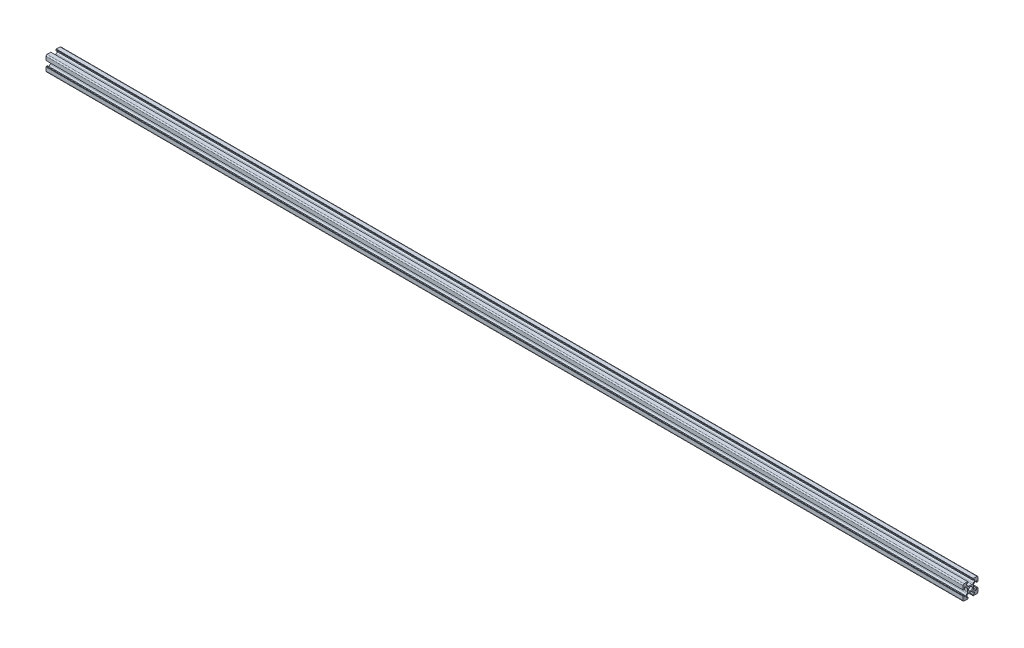
SolidWorks part; units mm, degrees
ref_plane "Front Plane" through (0, 0, 0) normal (1, 0, 0) x (0, 1, 0)
ref_plane "Top Plane" through (0, 0, 0) normal (0, 0, 1) x (0, 1, 0)
ref_plane "Right Plane" through (0, 0, 0) normal (0, 1, 0) x (-1, 0, 0)
sketch "Sketch2" plane through (0, 0, 0) normal (1, 0, 0) x (0, 1, 0)
  line L0 (-10, 3.6) -> (-9.5, 3.6)
  line L1 (-2.0109, -3.9) -> (2.0109, -3.9)
  line L2 (-3.9, -2.0109) -> (-3.9, 2.0109)
  line L3 (-2.0109, 3.9) -> (2.0109, 3.9)
  line L4 (3.9, -2.0109) -> (3.9, 2.0109)
  line L5 (-3.9, -3.9) -> (3.9, 3.9) construction
  line L6 (-3.9, 3.9) -> (3.9, -3.9) construction
  line L7 (-8.5, -10) -> (-3.6, -10)
  line L8 (-10, -8.5) -> (-10, -3.6)
  line L9 (-8.5, 10) -> (-3.6, 10)
  line L10 (10, -8.5) -> (10, -3.6)
  line L11 (-10, -10) -> (10, 10) construction
  line L12 (-10, 10) -> (10, -10) construction
  line L13 (-9.5, 3.6) -> (-9.5, 3.1)
  line L14 (-9.5, 3.1) -> (-8.2, 3.1)
  line L15 (-8.2, 3.1) -> (-8.2, 5.5)
  line L16 (-8.2, 5.5) -> (-6.5607, 5.5)
  line L17 (-6.5607, 5.5) -> (-4.4858, 3.4251)
  line L18 (3.6, 10) -> (3.6, 9.5)
  line L19 (-3.1, 9.5) -> (-3.1, 8.2)
  line L20 (-3.6, 9.5) -> (-3.1, 9.5)
  line L21 (-3.6, 10) -> (-3.6, 9.5)
  line L22 (-3.1, 8.2) -> (-5.5, 8.2)
  line L23 (-5.5, 8.2) -> (-5.5, 6.5607)
  line L24 (-5.5, 6.5607) -> (-3.4251, 4.4858)
  line L25 (3.6, 9.5) -> (3.1, 9.5)
  line L26 (3.1, 9.5) -> (3.1, 8.2)
  line L27 (3.1, 8.2) -> (5.5, 8.2)
  line L28 (5.5, 8.2) -> (5.5, 6.5607)
  line L29 (5.5, 6.5607) -> (3.4251, 4.4858)
  line L30 (6.5607, 5.5) -> (4.4858, 3.4251)
  line L31 (8.2, 5.5) -> (6.5607, 5.5)
  line L32 (8.2, 3.1) -> (8.2, 5.5)
  line L33 (9.5, 3.1) -> (8.2, 3.1)
  line L34 (9.5, 3.6) -> (9.5, 3.1)
  line L35 (10, 3.6) -> (9.5, 3.6)
  line L36 (10, -3.6) -> (9.5, -3.6)
  line L37 (9.5, -3.6) -> (9.5, -3.1)
  line L38 (9.5, -3.1) -> (8.2, -3.1)
  line L39 (8.2, -3.1) -> (8.2, -5.5)
  line L40 (8.2, -5.5) -> (6.5607, -5.5)
  line L41 (6.5607, -5.5) -> (4.4858, -3.4251)
  line L42 (5.5, -6.5607) -> (3.4251, -4.4858)
  line L43 (5.5, -8.2) -> (5.5, -6.5607)
  line L44 (3.1, -8.2) -> (5.5, -8.2)
  line L45 (3.1, -9.5) -> (3.1, -8.2)
  line L46 (3.6, -9.5) -> (3.1, -9.5)
  line L47 (3.6, -10) -> (3.6, -9.5)
  line L48 (-3.6, -10) -> (-3.6, -9.5)
  line L49 (-3.6, -9.5) -> (-3.1, -9.5)
  line L50 (-3.1, -9.5) -> (-3.1, -8.2)
  line L51 (-3.1, -8.2) -> (-5.5, -8.2)
  line L52 (-5.5, -8.2) -> (-5.5, -6.5607)
  line L53 (-5.5, -6.5607) -> (-3.4251, -4.4858)
  line L54 (-6.5607, -5.5) -> (-4.4858, -3.4251)
  line L55 (-8.2, -5.5) -> (-6.5607, -5.5)
  line L56 (-8.2, -3.1) -> (-8.2, -5.5)
  line L57 (-9.5, -3.1) -> (-8.2, -3.1)
  line L58 (-9.5, -3.6) -> (-9.5, -3.1)
  line L59 (-10, -3.6) -> (-9.5, -3.6)
  line L60 (-10, 3.6) -> (-10, 8.5)
  line L61 (3.6, 10) -> (8.5, 10)
  line L62 (10, 3.6) -> (10, 8.5)
  line L63 (3.6, -10) -> (8.5, -10)
  circle A0 centre (0, 0) radius 2.5
  arc A1 (-8.5, -10) -> (-10, -8.5) centre (-8.5, -8.5) cw
  arc A2 (8.5, 10) -> (10, 8.5) centre (8.5, 8.5) cw
  arc A3 (8.5, -10) -> (10, -8.5) centre (8.5, -8.5) ccw
  arc A4 (-10, 8.5) -> (-8.5, 10) centre (-8.5, 8.5) cw
  arc A5 (-4.4858, 3.4251) -> (-3.9, 2.0109) centre (-5.9, 2.0109) cw
  arc A6 (-4.4858, -3.4251) -> (-3.9, -2.0109) centre (-5.9, -2.0109) ccw
  arc A7 (-3.4251, -4.4858) -> (-2.0109, -3.9) centre (-2.0109, -5.9) cw
  arc A8 (3.4251, -4.4858) -> (2.0109, -3.9) centre (2.0109, -5.9) ccw
  arc A9 (4.4858, -3.4251) -> (3.9, -2.0109) centre (5.9, -2.0109) cw
  arc A10 (4.4858, 3.4251) -> (3.9, 2.0109) centre (5.9, 2.0109) ccw
  arc A11 (3.4251, 4.4858) -> (2.0109, 3.9) centre (2.0109, 5.9) cw
  arc A12 (-3.4251, 4.4858) -> (-2.0109, 3.9) centre (-2.0109, 5.9) ccw
  point P25 (-28.5352, 1.984)
  point P31 (0, 0)
  point P39 (0, 0)
  point P82 (0, 0)
  point P83 (0, 0)
  point P84 (0, 0)
  point P85 (0, 0)
  point P88 (-3.9, 2.8393)
  point P103 (-2.8393, 3.9)
  point P104 (-5.5, -6.5607)
  dimension "D1" = 5
  dimension "D6" = 1.5
  dimension "D14" = 2
  dimension "D15" = 2
  dimension "D2" = 7.8
  dimension "D3" = 7.8
  dimension "D4" = 20
  dimension "D5" = 20
  dimension "D8" = 1.5
  dimension "D9" = 11
  dimension "D10" = 7.2
  dimension "D11" = 6.2
  dimension "D12" = 0.5
  dimension "D13" = 1.8
  dimension "D16" = 3.9
  dimension "D17" = 3.9
  dimension "D7" = 4
extrude "Boss-Extrude1" add sketch "Sketch2" along normal blind 1219.2
